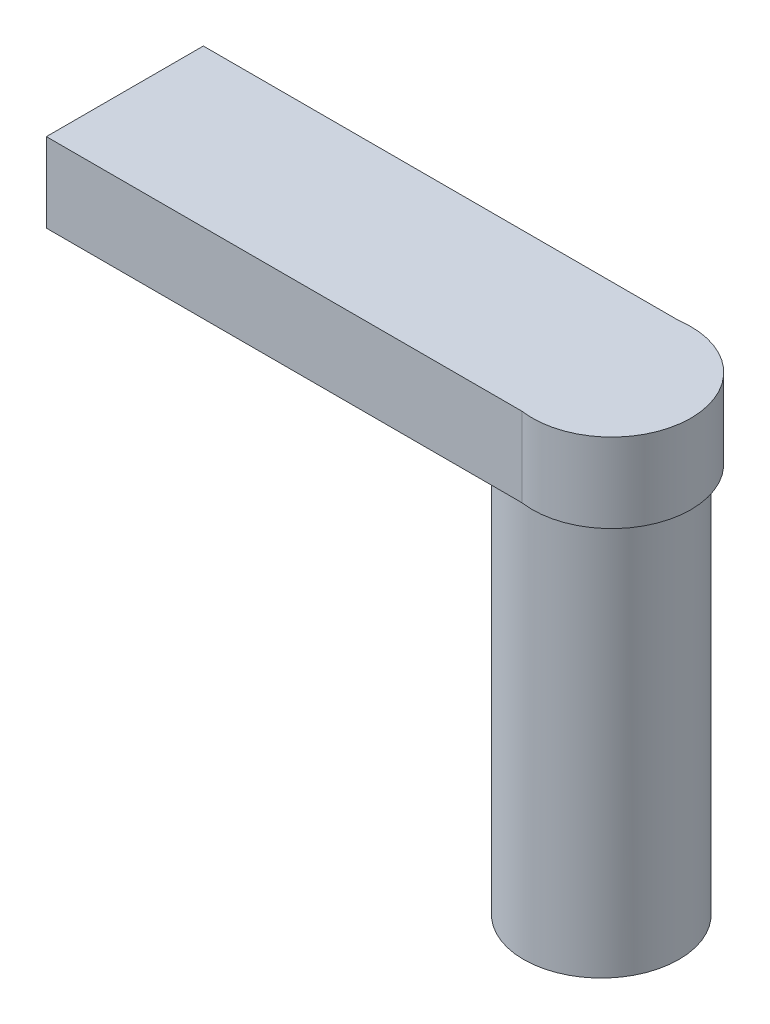
SolidWorks part; units mm, degrees
ref_plane "Front Plane" through (0, 0, 0) normal (0, 0, 1) x (1, 0, 0)
ref_plane "Top Plane" through (0, 0, 0) normal (0, 1, 0) x (1, 0, 0)
ref_plane "Right Plane" through (0, 0, 0) normal (1, 0, 0) x (0, 0, -1)
sketch "Sketch1" plane through (0, 0, 0) normal (0, 1, 0) x (1, 0, 0)
  circle A0 centre (0, 0) radius 4.9
  dimension "D1" = 9.8
extrude "Boss-Extrude1" add sketch "Sketch1" along normal blind 25
sketch "Sketch2" plane through (0, 25, 0) normal (0, 1, 0) x (1, 0, 0)
  line L1 (0, 4.9) -> (-30, 4.9)
  line L3 (0, -5) -> (-30, -5)
  line L4 (-30, 4.9) -> (-30, -5)
  circle A0 centre (0, 0) radius 4.9 construction
  arc A1 (0, -5) -> (0, 4.9) centre (0.7053, -0.05) ccw
  dimension "D1" = 30
extrude "Boss-Extrude2" add sketch "Sketch2" along normal blind 5
